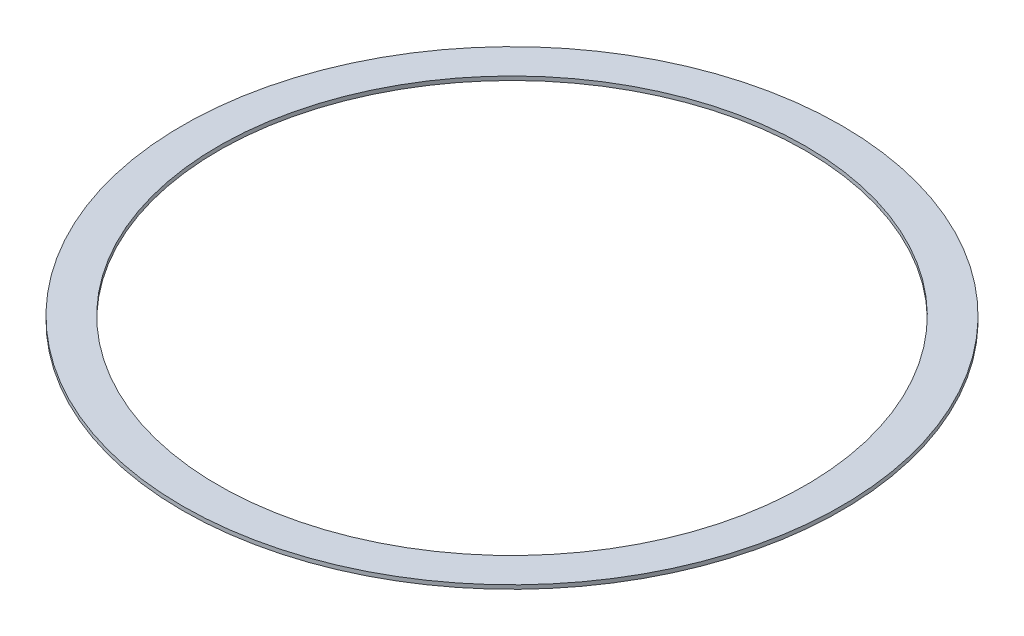
SolidWorks part; units mm, degrees
material "PTFE (general)"
ref_plane "Front Plane" through (0, 0, 0) normal (0, 0, 1) x (1, 0, 0)
ref_plane "Top Plane" through (0, 0, 0) normal (0, 1, 0) x (1, 0, 0)
ref_plane "Right Plane" through (0, 0, 0) normal (1, 0, 0) x (0, 0, -1)
sketch "Sketch1" plane through (0, 0, 0) normal (0, 1, 0) x (1, 0, 0)
  circle A1 centre (0, 0) radius 57.15
  circle A2 centre (0, 0) radius 64.135
  dimension "D2" = 114.3
  dimension "D1" = 6.985
extrude "Boss-Extrude1" add sketch "Sketch1" along normal blind 0.762 contours A2 A1
equation "\"Middle Coupler Inner Daimeter\"= 3.875in"
equation "\"Middle Coupler  Wall Thickness\" = 0.25in"
equation "\"Middle Coupler Bottom Thickness\"= 0.2in"
equation "\"Bearing Rail Offset\"= 0.45in"
equation "\"3-56 UNF Tap\"= 0.089in"
equation "\"3-48 Tap\"= 0.079in"
equation "\"3-56 UNF Clearance\"= 0.104in"
equation "\"3-48 Clearance\" = 0.104in"
equation "\"Ball Bearing Distance\"= 0.03in"
equation "\"TCA Outer Diameter\" = 6in"
equation "\"Interstage Aeroframe Wall Thickness\" = 0.072in"
equation "\"Compression Spring OD\"= 0.42in"
equation "\"10-24 Tap\"= 0.157in"
equation "\"10-24 Clearance\"= 0.196in"
equation "\"Lower Stage Fuselage Wall Thickness\" = 0.25in"
equation "\"6-32 Tap\" = 0.107in"
equation "\"6-32 Clearance\" = 0.144"
equation "\"1/4-20 Tap\" = 0.201in"
equation "\"12-24 Tap\" = 0.177in"
equation "\"D2@Sketch1\"=\"Middle Coupler Inner Daimeter\"+0.625in"
equation "\"D1@Sketch1\"=0.275"
